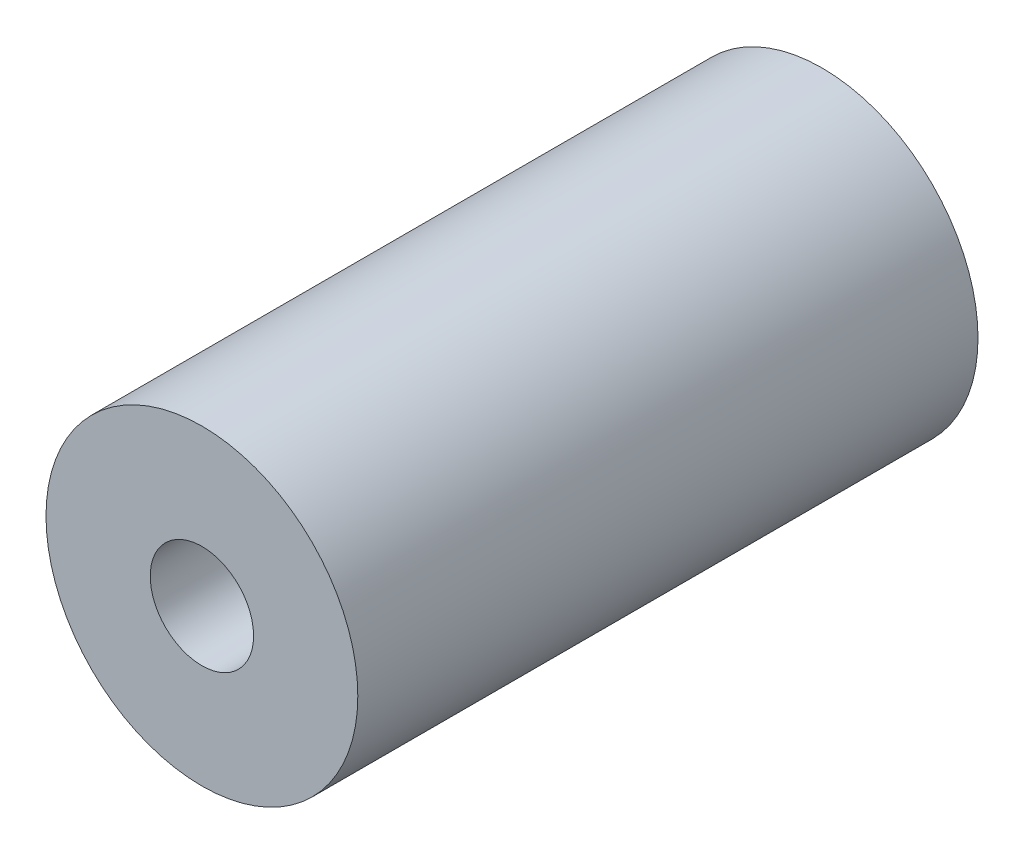
SolidWorks part; units mm, degrees
ref_plane "Front Plane" through (0, 0, 0) normal (0, 0, 1) x (1, 0, 0)
ref_plane "Top Plane" through (0, 0, 0) normal (0, 1, 0) x (1, 0, 0)
ref_plane "Right Plane" through (0, 0, 0) normal (1, 0, 0) x (0, 0, -1)
sketch "Sketch1" plane through (0, 0, 0) normal (0, 0, 1) x (1, 0, 0)
  circle A0 centre (-63.5941, 24.957) radius 4.525
extrude "Boss-Extrude1" add sketch "Sketch1" along normal blind 18
sketch "Sketch2" plane through (0, 0, 18) normal (0, 0, 1) x (1, 0, 0)
  circle A0 centre (-63.5941, 24.957) radius 1.5
extrude "Cut-Extrude1" cut sketch "Sketch2" against normal blind 18
